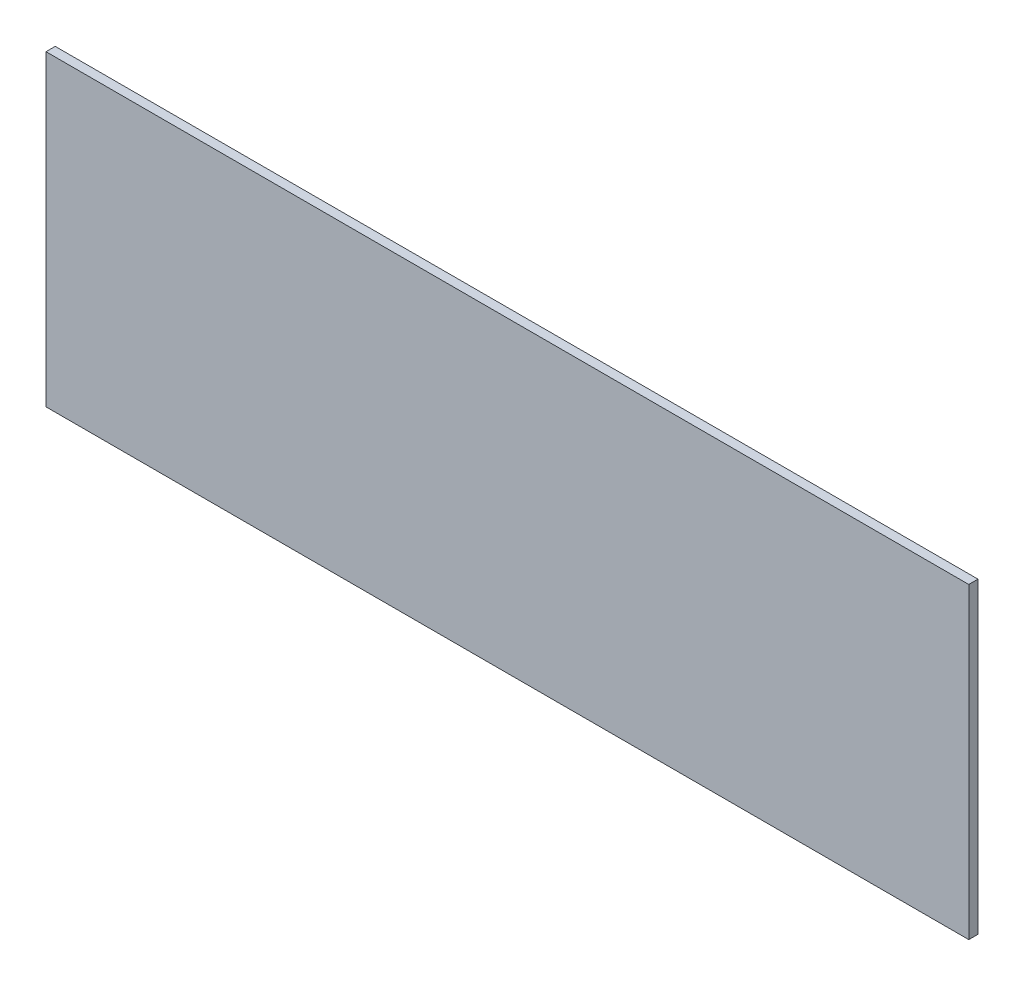
SolidWorks part; units mm, degrees
material "Chapa F.F 1020 - 1,5 mm"
ref_plane "Plano frontal" through (0, 0, 0) normal (0, 0, 1) x (1, 0, 0)
ref_plane "Plano superior" through (0, 0, 0) normal (0, 1, 0) x (1, 0, 0)
ref_plane "Plano direito" through (0, 0, 0) normal (1, 0, 0) x (0, 0, -1)
sketch "Esboço1" plane through (0, 0, 0) normal (0, 0, 1) x (1, 0, 0)
  line L1 (0, 0) -> (150, 0)
  line L2 (0, 0) -> (0, 50)
  line L3 (0, 50) -> (150, 50)
  line L4 (150, 0) -> (150, 50)
  dimension "D1" = 150
  dimension "D2" = 50
extrude "Ressalto-extrusão1" add sketch "Esboço1" along normal blind 1.5
